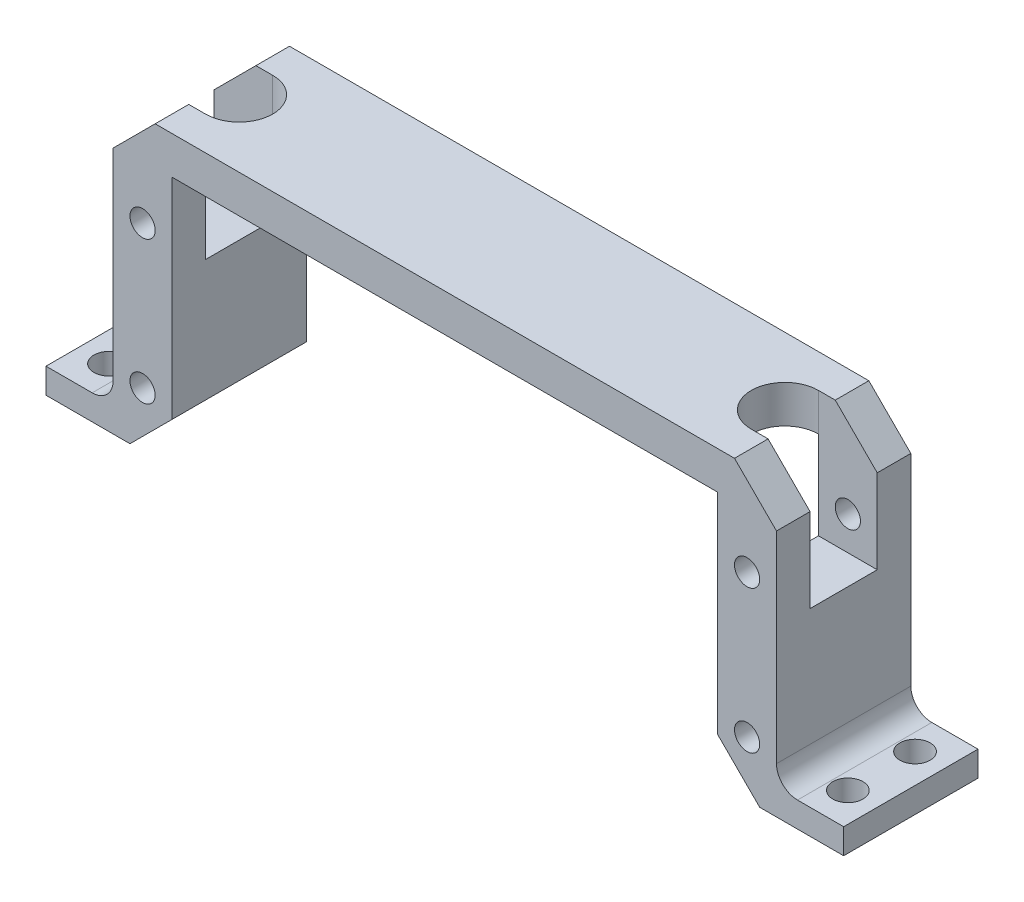
SolidWorks part; units mm, degrees
other "Markup1"
sketch "Sketch6" plane through (-36, 25, 8) normal (-0.8707, 0.2235, 0.4381) x (0.4473, -0.0107, 0.8943)
material "Nylon PA 12"
ref_plane "Front Plane" through (0, 0, 0) normal (0, 0, 1) x (1, 0, 0)
ref_plane "Top Plane" through (0, 0, 0) normal (0, 1, 0) x (1, 0, 0)
ref_plane "Right Plane" through (0, 0, 0) normal (1, 0, 0) x (0, 0, -1)
sketch "Sketch1" plane through (0, 0, 0) normal (0, 0, 1) x (1, 0, 0)
  line L0 (-47.5, 0) -> (-32.5, 0)
  line L1 (-32.5, 0) -> (-32.5, 30)
  line L2 (-32.5, 30) -> (32.5, 30)
  line L3 (32.5, 30) -> (32.5, 0)
  line L4 (32.5, 0) -> (47.5, 0)
  line L5 (-47.5, 0) -> (-47.5, 3)
  line L6 (-47.5, 3) -> (-39.5, 3)
  line L7 (47.5, 0) -> (47.5, 3)
  line L8 (47.5, 3) -> (39.5, 3)
  line L9 (-39.5, 3) -> (-39.5, 34.5)
  line L10 (-39.5, 34.5) -> (39.5, 34.5)
  line L11 (39.5, 34.5) -> (39.5, 3)
  dimension "D1" = 95
  dimension "D2" = 15
  dimension "D3" = 65
  dimension "D4" = 32.5
  dimension "D5" = 30
  dimension "D6" = 3
  dimension "D7" = 15
  dimension "D8" = 4.5
  dimension "D9" = 7
  dimension "D10" = 7
extrude "Boss-Extrude1" add sketch "Sketch1" along normal mid plane 16
chamfer "Chamfer5" distance 5 angle 45 4 edges at (-39.5, 34.5, 0) (32.5, 0, 0) (-32.5, 0, 0) (39.5, 34.5, 0)
fillet "Fillet1" radius 2.5 2 edges at (39.5, 3, 0) (-39.5, 3, 0)
sketch "Sketch2" plane through (0, 0, 8) normal (0, 0, 1) x (1, 0, 0)
  line L2 (36, 37.1974) -> (36, -3.6862) construction
  circle A2 centre (36, 23.5) radius 1.5
  circle A3 centre (36, 6.5) radius 1.5
  dimension "D1" = 36
  dimension "D2" = 6.5
  dimension "D3" = 17
extrude "Cut-Extrude1" cut sketch "Sketch2" against normal through all
mirror "Mirror1" about plane through (0, 0, 0) normal (1, 0, 0) of "Cut-Extrude1"
sketch "Sketch3" plane through (0, 3, 0) normal (0, 1, 0) x (1, 0, 0)
  line L0 (47.5, -8) -> (47.5, 8) construction
  line L1 (42, 28.8859) -> (42, -25.0715) construction
  line L2 (-42, 27.8941) -> (-42, -24.0796) construction
  line L3 (-42, -8) -> (-42, 8) construction
  line L4 (42, 8) -> (42, -8) construction
  line L5 (56.6832, -8) -> (-41.1826, -8) construction
  line L6 (65.7079, 8) -> (-46.658, 8) construction
  line L7 (47.5, 8) -> (42, 8) construction
  line L8 (47.5, -8) -> (42, -8) construction
  line L9 (47.5, 29.9064) -> (47.5, -19.7738) construction
  circle A0 centre (44, 4) radius 1.8
  circle A1 centre (44, -4) radius 1.8
  circle A2 centre (-44, 4) radius 1.8
  circle A3 centre (-44, -4) radius 1.8
  dimension "D2" = 3.6
  dimension "D3" = 3.6
  dimension "D12" = 3.6
  dimension "D14" = 3.6
  dimension "D1" = 2
  dimension "D4" = 16
  dimension "D5" = 4
  dimension "D6" = 4
  dimension "D7" = 5.5
  dimension "D8" = 2
  dimension "D9" = 4
  dimension "D10" = 12
  dimension "D11" = 16
  dimension "D13" = 3.5
  dimension "D15" = 84
extrude "Cut-Extrude2" cut sketch "Sketch3" against normal through all
sketch "Sketch5" plane through (0, 34.5, 0) normal (0, 1, 0) x (1, 0, 0)
  line L0 (-39.5, -8) -> (-39.5, 8) construction
  line L6 (-44, 4) -> (-39.5, 4) construction
  line L7 (44, 4) -> (44, -4) construction
  line L8 (44, -4) -> (39.5, -4) construction
  line L9 (-44, -4) -> (-44, 4) construction
  line L13 (39.5, 8) -> (39.5, -8) construction
  line L18 (-39.5, -4) -> (-44, -4) construction
  line L21 (39.5, 4) -> (44, 4) construction
  line L32 (32.5, -8) -> (32.5, 8) construction
  line L33 (39.5, 4) -> (32.5, 4)
  line L34 (39.5, 4) -> (39.5, -4)
  line L35 (39.5, -4) -> (32.5, -4)
  line L36 (32.5, 4) -> (32.5, -4)
  line L37 (-32.5, -8) -> (-32.5, 8) construction
  line L38 (-39.5, 4) -> (-32.5, 4)
  line L39 (-39.5, 4) -> (-39.5, -4)
  line L40 (-39.5, -4) -> (-32.5, -4)
  line L41 (-32.5, 4) -> (-32.5, -4)
extrude "Cut-Extrude3" cut sketch "Sketch5" against normal blind 15
sketch "Sketch7" plane through (0, 34.5, 0) normal (0, 1, 0) x (1, 0, 0)
  line L0 (-34.5, 4) -> (-34.5, -4) construction
  line L1 (-32.5, -4) -> (-32.5, 4) construction
  line L2 (32.5, 4) -> (32.5, -4) construction
  line L3 (32.5, 4) -> (32.5, -4)
  line L4 (-32.5, 4) -> (-32.5, -4)
  arc A0 (-32.5, -4) -> (-32.5, 4) centre (-32.5, 0) ccw
  arc A1 (32.5, 4) -> (32.5, -4) centre (32.5, 0) ccw
extrude "Cut-Extrude5" cut sketch "Sketch7" against normal blind 15
